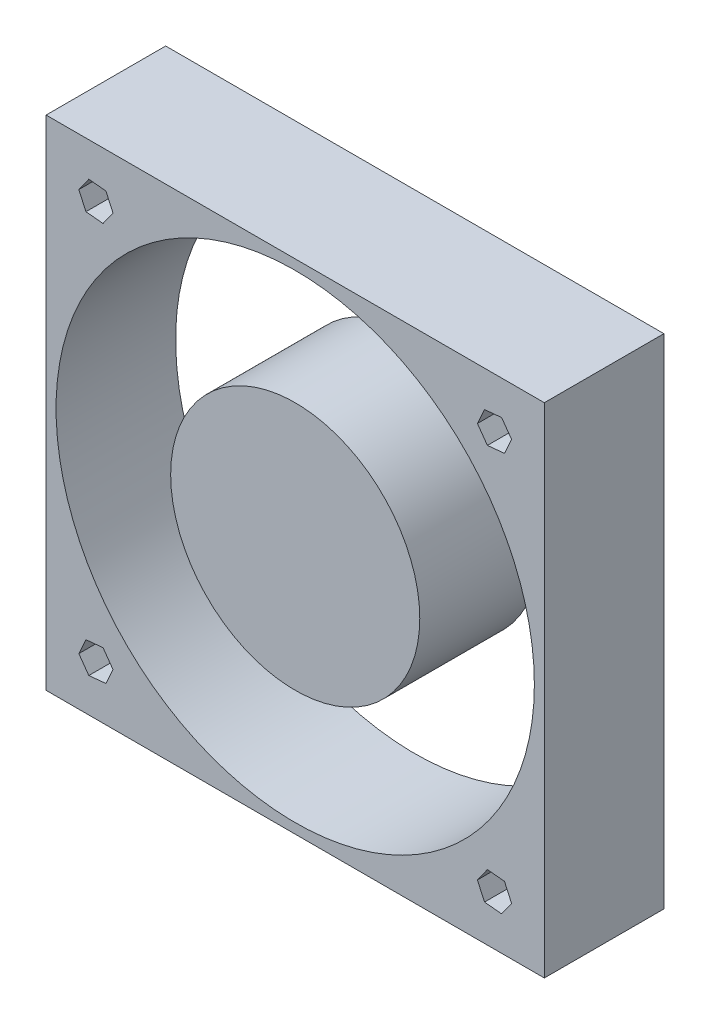
SolidWorks part; units mm, degrees
ref_plane "前视基准面" through (0, 0, 0) normal (0, 0, 1) x (1, 0, 0)
ref_plane "上视基准面" through (0, 0, 0) normal (0, 1, 0) x (1, 0, 0)
ref_plane "右视基准面" through (0, 0, 0) normal (1, 0, 0) x (0, 0, -1)
sketch "草图1" plane through (0, 0, 0) normal (0, 0, 1) x (1, 0, 0)
  line L0 (0, 0) -> (0, 42.5311) construction
  line L1 (-25, 25) -> (25, 25)
  line L2 (-25, 25) -> (-25, -25)
  line L3 (-25, -25) -> (25, -25)
  line L4 (25, 25) -> (25, -25)
  line L5 (0, 0) -> (58.5689, 0) construction
  dimension "D1" = 50
extrude "凸台-拉伸1" add sketch "草图1" along normal blind 12
sketch "草图2" plane through (0, 0, 12) normal (0, 0, 1) x (1, 0, 0)
  circle A0 centre (0, 0) radius 24
  circle A1 centre (0, 0) radius 12.5
  dimension "D1" = 48
  dimension "D2" = 25
extrude "切除-拉伸1" cut sketch "草图2" against normal through all
sketch "草图3" plane through (0, 0, 12) normal (0, 0, 1) x (1, 0, 0)
  line L0 (0, 0) -> (0, 30.1085) construction
  line L1 (-18.9984, 21.4022) -> (-20.7136, 21.5685)
  line L2 (-20.7136, 21.5685) -> (-21.7151, 20.1663)
  line L3 (-21.7151, 20.1663) -> (-21.0016, 18.5978)
  line L4 (-21.0016, 18.5978) -> (-19.2864, 18.4315)
  line L5 (-19.2864, 18.4315) -> (-18.2849, 19.8337)
  line L6 (-18.2849, 19.8337) -> (-18.9984, 21.4022)
  line L7 (0, 0) -> (-34.0603, 0) construction
  line L8 (-18.2849, -19.8337) -> (-18.9984, -21.4022)
  line L9 (-19.2864, -18.4315) -> (-18.2849, -19.8337)
  line L10 (-21.0016, -18.5978) -> (-19.2864, -18.4315)
  line L11 (-21.7151, -20.1663) -> (-21.0016, -18.5978)
  line L12 (-20.7136, -21.5685) -> (-21.7151, -20.1663)
  line L13 (-18.9984, -21.4022) -> (-20.7136, -21.5685)
  line L14 (18.9984, -21.4022) -> (20.7136, -21.5685)
  line L15 (20.7136, -21.5685) -> (21.7151, -20.1663)
  line L16 (21.7151, -20.1663) -> (21.0016, -18.5978)
  line L17 (21.0016, -18.5978) -> (19.2864, -18.4315)
  line L18 (19.2864, -18.4315) -> (18.2849, -19.8337)
  line L19 (18.2849, -19.8337) -> (18.9984, -21.4022)
  line L20 (18.2849, 19.8337) -> (18.9984, 21.4022)
  line L21 (19.2864, 18.4315) -> (18.2849, 19.8337)
  line L22 (21.0016, 18.5978) -> (19.2864, 18.4315)
  line L23 (21.7151, 20.1663) -> (21.0016, 18.5978)
  line L24 (20.7136, 21.5685) -> (21.7151, 20.1663)
  line L25 (18.9984, 21.4022) -> (20.7136, 21.5685)
  circle A0 centre (-20, 20) radius 1.4923 construction
  circle A1 centre (-20, -20) radius 1.4923 construction
  circle A2 centre (20, -20) radius 1.4923 construction
  circle A3 centre (20, 20) radius 1.4923 construction
  dimension "D1" = 40
  dimension "D2" = 40
extrude "切除-拉伸2" cut sketch "草图3" against normal blind 10
sketch "草图4" plane through (0, 0, 12) normal (0, 0, 1) x (1, 0, 0)
  line L0 (0, 0) -> (0, 35.2175) construction
  line L1 (0, 0) -> (-46.2326, 0) construction
  line L2 (-20.7136, 21.5685) -> (-19.2864, 18.4315) construction
  circle A0 centre (-20, 20) radius 1
  circle A1 centre (-20, -20) radius 1
  circle A2 centre (20, -20) radius 1
  circle A3 centre (20, 20) radius 1
  dimension "D1" = 2
extrude "切除-拉伸3" cut sketch "草图4" against normal through all
